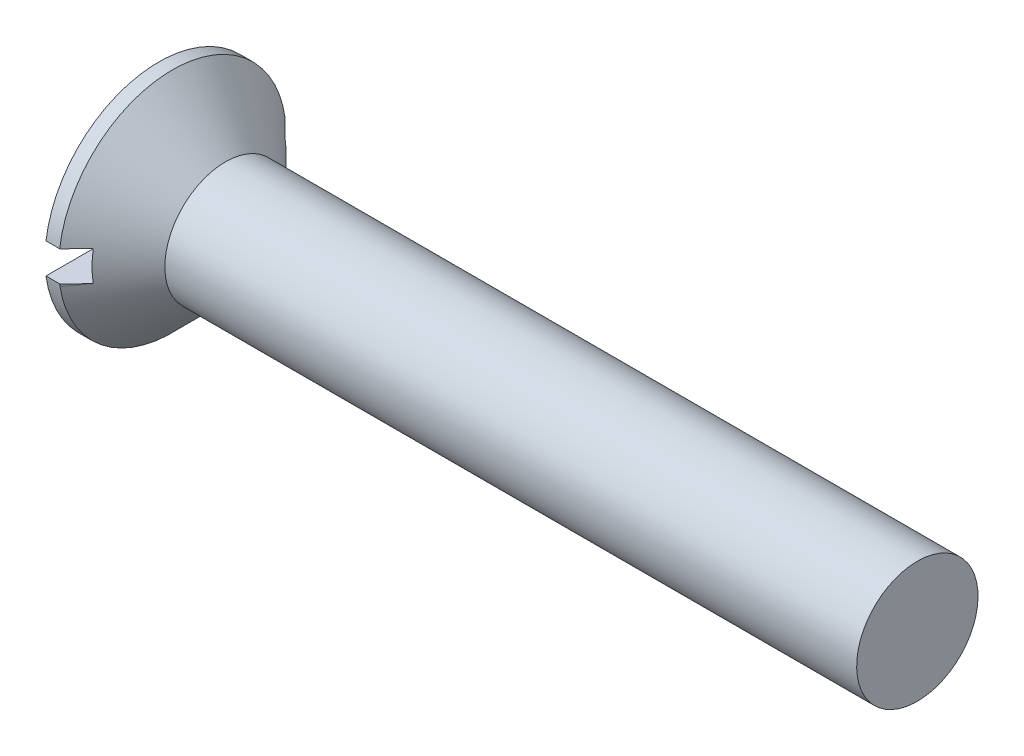
SolidWorks part; units mm, degrees
material "Plain Carbon Steel"
ref_plane "Front Plane" through (0, 0, 0) normal (0, 0, 1) x (1, 0, 0)
ref_plane "Top Plane" through (0, 0, 0) normal (0, 1, 0) x (1, 0, 0)
ref_plane "Right Plane" through (0, 0, 0) normal (1, 0, 0) x (0, 0, -1)
sketch "Sketch1" plane through (0, 0, 0) normal (0, 0, 1) x (1, 0, 0)
  line L0 (0, 0) -> (0, 3.75)
  line L1 (0, 3.75) -> (0.45, 3.75)
  line L2 (0.45, 3.75) -> (2.2, 2)
  line L3 (2.2, 2) -> (25, 2)
  line L4 (25, 2) -> (25, 0)
  line L5 (25, 0) -> (0, 0) construction
  line L6 (0, 0) -> (25, 0)
  dimension "D1" = 45
  dimension "D2" = 4
  dimension "D3" = 7.5
  dimension "D4" = 2.2
  dimension "D5" = 25
revolve "Revolve1" add sketch "Sketch1" angle 360 about L5
sketch "Sketch2" plane through (0, 0, 0) normal (-1, 0, 0) x (0, 0, 1)
  line L0 (3.75, 0) -> (-3.75, 0) construction
  line L1 (-3.75, 0.5) -> (3.75, 0.5)
  line L2 (-3.75, 0.5) -> (-3.75, -0.5)
  line L3 (-3.75, -0.5) -> (3.75, -0.5)
  line L4 (3.75, 0.5) -> (3.75, -0.5)
  circle A0 centre (0, 0) radius 3.75 construction
  dimension "D1" = 1
extrude "Cut-Extrude1" cut sketch "Sketch2" against normal blind 1
